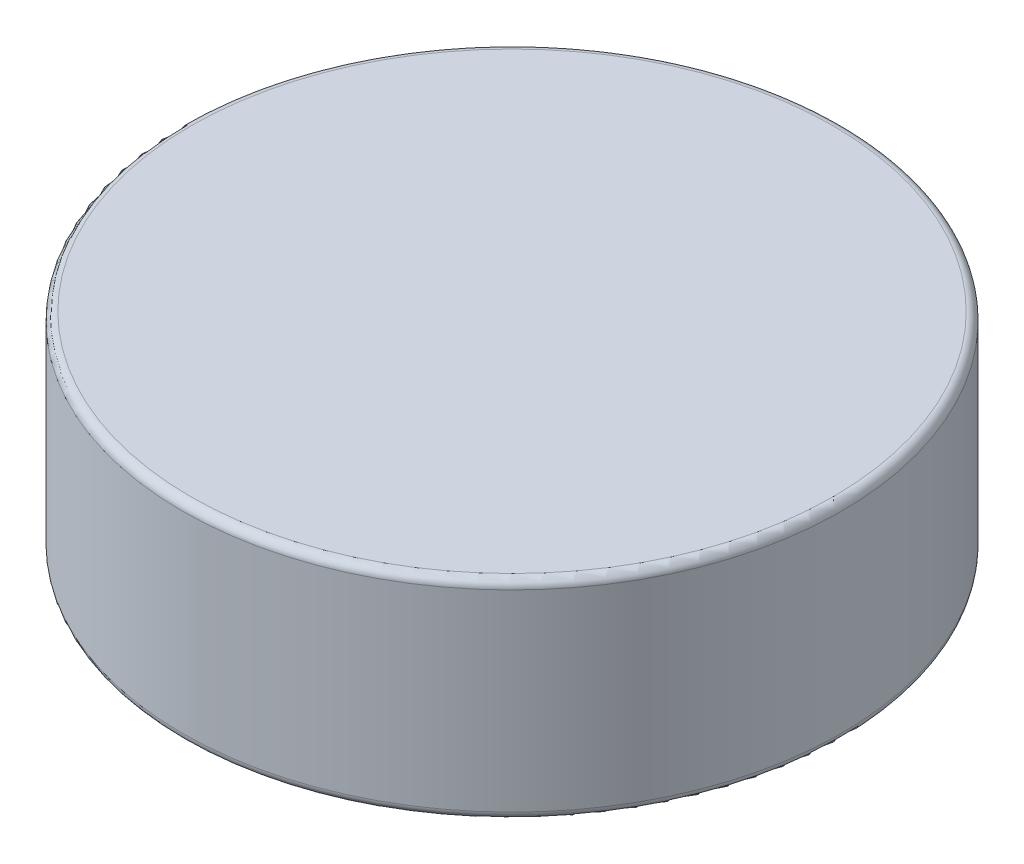
SolidWorks part; units mm, degrees
ref_plane "Front Plane" through (0, 0, 0) normal (0, 0, 1) x (1, 0, 0)
ref_plane "Top Plane" through (0, 0, 0) normal (0, 1, 0) x (1, 0, 0)
ref_plane "Right Plane" through (0, 0, 0) normal (1, 0, 0) x (0, 0, -1)
sketch "Sketch1" plane through (0, 0, 0) normal (0, 1, 0) x (1, 0, 0)
  circle A0 centre (0, 0) radius 5.0038
  dimension "D1" = 10.0076
extrude "Boss-Extrude1" add sketch "Sketch1" along normal blind 3.175
fillet "Fillet1" radius 0.127 2 edges at (0, 0, 5.0038) (0, 3.175, 5.0038)
